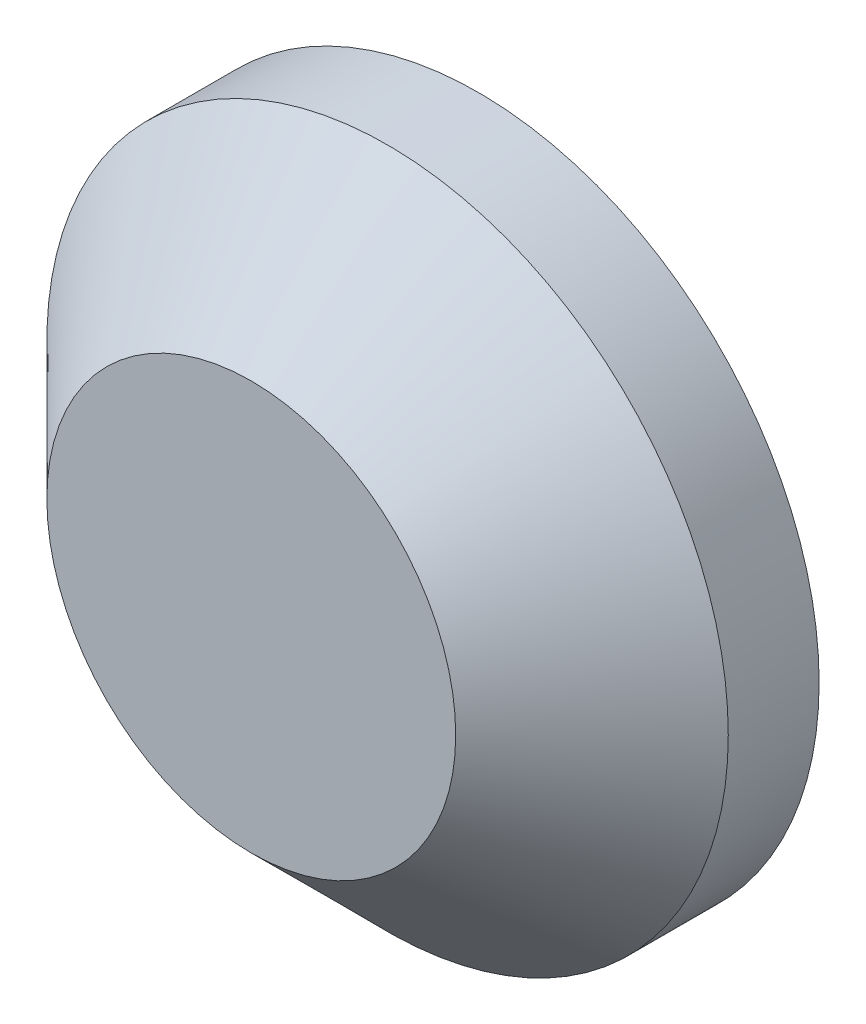
SolidWorks part; units mm, degrees
ref_plane "Front Plane" through (0, 0, 0) normal (0, 0, 1) x (1, 0, 0)
ref_plane "Top Plane" through (0, 0, 0) normal (0, 1, 0) x (1, 0, 0)
ref_plane "Right Plane" through (0, 0, 0) normal (1, 0, 0) x (0, 0, -1)
sketch "Sketch1" plane through (0, 0, 0) normal (0, 0, 1) x (1, 0, 0)
  circle A0 centre (0, 0) radius 7.5
  dimension "D1" = 15
extrude "Boss-Extrude1" add sketch "Sketch1" along normal blind 5
chamfer "Chamfer1" distance 3 angle 45 1 edges at (7.5, 0, 5)
